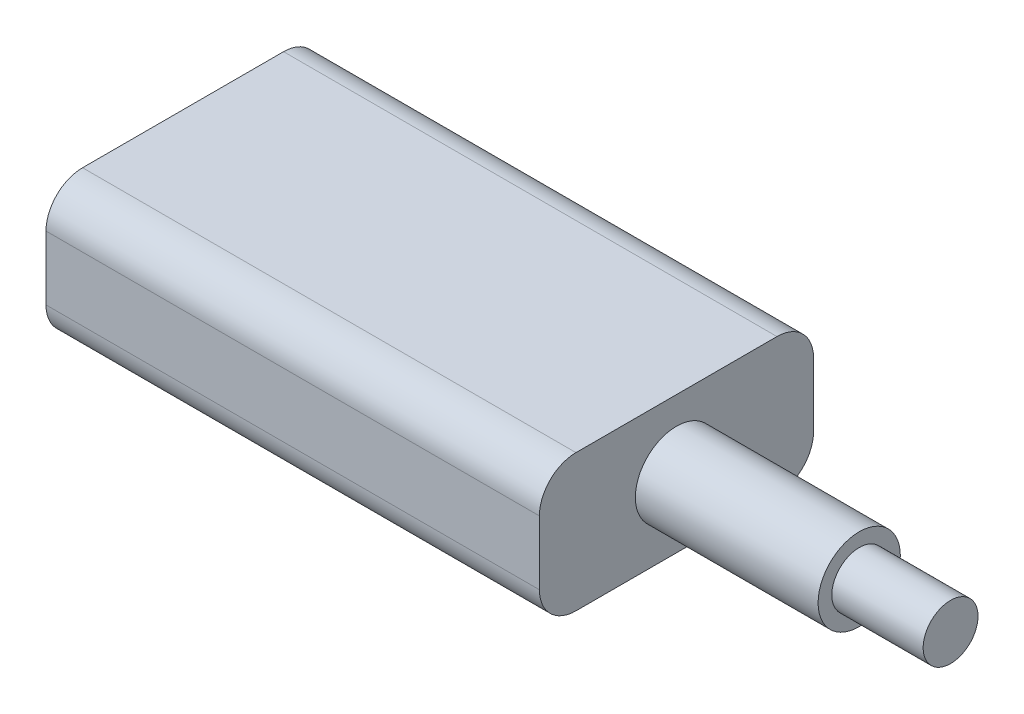
SolidWorks part; units mm, degrees
ref_plane "Спереди" through (0, 0, 0) normal (0, 0, 1) x (1, 0, 0)
ref_plane "Сверху" through (0, 0, 0) normal (0, 1, 0) x (1, 0, 0)
ref_plane "Справа" through (0, 0, 0) normal (1, 0, 0) x (0, 0, -1)
sketch "Эскиз1" plane through (0, 0, 0) normal (0, 1, 0) x (1, 0, 0)
  line L0 (0, 0) -> (0, 15)
  line L1 (0, 15) -> (27, 15)
  line L2 (27, 15) -> (27, 0)
  line L3 (27, 0) -> (0, 0)
extrude "Бобышка-Вытянуть1" add sketch "Эскиз1" along normal blind 7.5
sketch "Эскиз2" plane through (27, 0, 0) normal (1, 0, 0) x (0, 0, -1)
  line L0 (0, 7.5) -> (15, 0) construction
  line L1 (15, 0) -> (15, 7.5)
  line L2 (15, 7.5) -> (0, 0) construction
  circle A0 centre (7.5, 3.75) radius 2.25
extrude "Бобышка-Вытянуть2" add sketch "Эскиз2" along normal blind 10 contours A0
sketch "Эскиз3" plane through (37, 0, 0) normal (1, 0, 0) x (0, 0, -1)
  circle A0 centre (7.5, 3.75) radius 1.5
extrude "Бобышка-Вытянуть3" add sketch "Эскиз3" along normal blind 5
fillet "Скругление1" radius 2 4 edges at (13.5, 0, 0) (13.5, 0, -15) (13.5, 7.5, 0) (13.5, 7.5, -15)
sketch "Эскиз4" plane through (0, 0, 0) normal (-1, 0, 0) x (0, 0, 1)
  line L0 (-13, 7.5) -> (-13, 3.5) construction
  line L1 (-2, 7.5) -> (-2, 3.5) construction
  line L2 (-2, 3.5) -> (-13, 3.5)
  line L3 (-13, 3.5) -> (-13, 6.5)
  line L4 (-13, 6.5) -> (-2, 6.5)
  line L5 (-2, 6.5) -> (-2, 3.5)
extrude "Вырез-Вытянуть1" cut sketch "Эскиз4" against normal blind 10
ref_plane "Плоскость1" through (0, 0, -7.5) normal (0, 0, 1) x (1, 0, 0)
